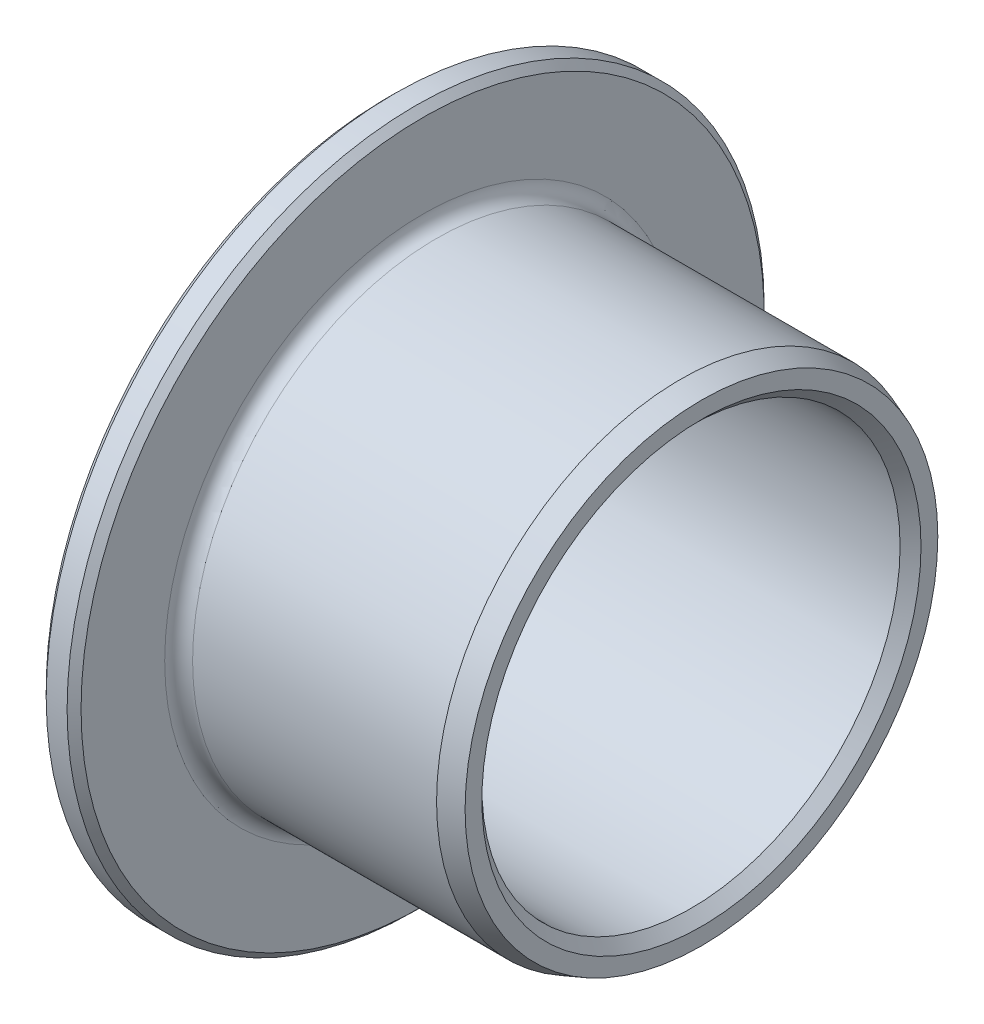
SolidWorks part; units mm, degrees
ref_plane "Face" through (0, 0, 0) normal (0, 0, 1) x (1, 0, 0)
ref_plane "Dessus" through (0, 0, 0) normal (0, 1, 0) x (1, 0, 0)
ref_plane "Droite" through (0, 0, 0) normal (1, 0, 0) x (0, 0, -1)
sketch "Esquisse1" plane through (0, 0, 0) normal (0, 0, 1) x (1, 0, 0)
  line L0 (-1, 6) -> (-1, 10)
  line L1 (-1, 10) -> (0, 10)
  line L2 (0, 10) -> (0, 7)
  line L3 (0, 7) -> (8, 7)
  line L4 (8, 7) -> (8, 6)
  line L5 (8, 6) -> (-1, 6)
  line L6 (-5.3127, 0) -> (18.9323, 0) construction
  dimension "D1" = 10
  dimension "D2" = 6
  dimension "D3" = 1
  dimension "D4" = 7
  dimension "D5" = 9
revolve "Base-Révolution" add sketch "Esquisse1" angle 360 about L6
chamfer "Chanfrein2" distance 0.6 angle 20 1 edges at (8, 0, 7)
chamfer "Chanfrein3" distance 0.3 angle 45 2 edges at (-1, 0, 6) (8, 0, 6)
chamfer "Chanfrein4" distance 0.2 angle 45 2 edges at (0, 0, 10) (-1, 0, 10)
fillet "Congé1" radius 0.4 1 edges at (0, 0, 7)
